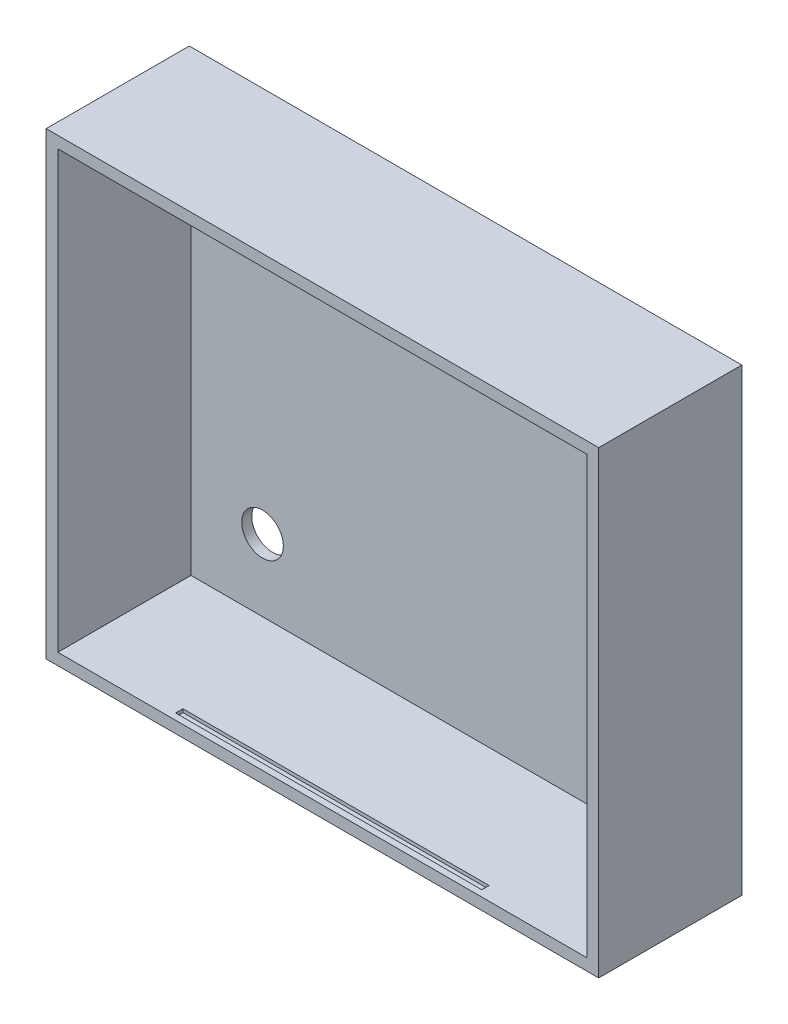
SolidWorks part; units mm, degrees
ref_plane "정면" through (0, 0, 0) normal (0, 0, 1) x (1, 0, 0)
ref_plane "윗면" through (0, 0, 0) normal (0, 1, 0) x (1, 0, 0)
ref_plane "우측면" through (0, 0, 0) normal (1, 0, 0) x (0, 0, -1)
sketch "스케치1" plane through (0, 0, 0) normal (0, 0, 1) x (1, 0, 0)
  line L1 (-83, -69) -> (83, -69)
  line L2 (-83, -69) -> (-83, 69)
  line L3 (-83, 69) -> (83, 69)
  line L4 (83, -69) -> (83, 69)
  line L5 (-83, -69) -> (83, 69) construction
  line L6 (-83, 69) -> (83, -69) construction
  point P0 (0, 0)
  dimension "D1" = 166
  dimension "D2" = 138
extrude "보스-돌출1" add sketch "스케치1" along normal blind 3
sketch "스케치2" plane through (0, 0, 3) normal (0, 0, 1) x (1, 0, 0)
  line L1 (-83, -69) -> (83, -69)
  line L2 (-83, -69) -> (-83, 69)
  line L3 (-83, 69) -> (83, 69)
  line L4 (83, -69) -> (83, 69)
  line L5 (-83, -69) -> (83, 69) construction
  line L6 (-83, 69) -> (83, -69) construction
  line L7 (-79.5, -65.5) -> (79.5, -65.5)
  line L8 (-79.5, -65.5) -> (-79.5, 65.5)
  line L9 (-79.5, 65.5) -> (79.5, 65.5)
  line L10 (79.5, -65.5) -> (79.5, 65.5)
  line L11 (-79.5, -65.5) -> (79.5, 65.5) construction
  line L12 (-79.5, 65.5) -> (79.5, -65.5) construction
  point P0 (0, 0)
  point P7 (0, 0)
  line M9 (83, -69) -> (83, 69)
  line M10 (83, 69) -> (-83, 69)
  line M11 (-83, 69) -> (-83, -69)
  line M12 (-83, -69) -> (83, -69)
  dimension "D1" = 159
  dimension "D2" = 131
extrude "보스-돌출2" add sketch "스케치2" along normal blind 40 contours L10 L7 L8 L9 M12 M9 M10 M11
sketch "스케치3" plane through (0, 0, 3) normal (0, 0, 1) x (1, 0, 0)
  line L0 (-83, 69) -> (-83, -69) construction
  line L1 (83, 69) -> (-83, 69) construction
  line L2 (0, 0) -> (-67.1963, 0) construction
  line L3 (0, 0) -> (0, -54.1905) construction
  circle A1 centre (-58, 44) radius 6.25
  circle A2 centre (-58, -44) radius 6.25
  circle A3 centre (58, -44) radius 6.25
  circle A4 centre (58, 44) radius 6.25
  dimension "D2" = 25
  dimension "D3" = 12.5
  dimension "D1" = 25
extrude "컷-돌출4" cut sketch "스케치3" against normal up to next
sketch "스케치4" plane through (0, 65.5, 0) normal (0, -1, 0) x (1, 0, 0)
  line L0 (-79.5, 43) -> (79.5, 43) construction
  line L1 (-46, 41.1) -> (46, 41.1)
  line L2 (-46, 41.1) -> (-46, 38.9)
  line L3 (-46, 38.9) -> (46, 38.9)
  line L4 (46, 41.1) -> (46, 38.9)
  line L5 (-46, 41.1) -> (46, 38.9) construction
  line L6 (-46, 38.9) -> (46, 41.1) construction
  point P0 (0, 40)
  dimension "D1" = 3
  dimension "D2" = 2.2
  dimension "D3" = 92
extrude "컷-돌출5" cut sketch "스케치4" against normal blind 1
sketch "스케치5" plane through (0, -65.5, 0) normal (0, 1, 0) x (1, 0, 0)
  line L0 (-79.5, -43) -> (79.5, -43) construction
  line L1 (-46.015, -38.9) -> (45.985, -38.9)
  line L2 (-46.015, -38.9) -> (-46.015, -41.1)
  line L3 (-46.015, -41.1) -> (45.985, -41.1)
  line L4 (45.985, -38.9) -> (45.985, -41.1)
  line L5 (-46.015, -38.9) -> (45.985, -41.1) construction
  line L6 (-46.015, -41.1) -> (45.985, -38.9) construction
  point P0 (-0.015, -40)
  point P7 (0, -43)
  dimension "D1" = 92
  dimension "D2" = 3
  dimension "D3" = 2.2
extrude "컷-돌출6" cut sketch "스케치5" against normal blind 1
